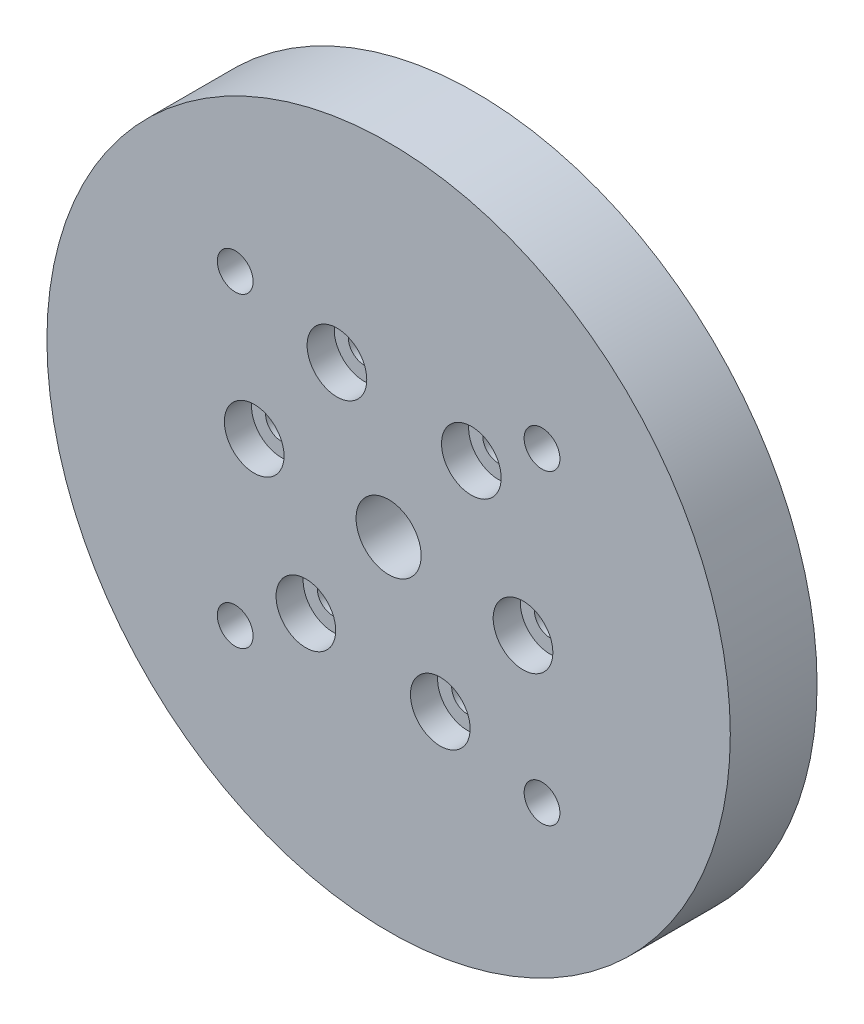
SolidWorks part; units mm, degrees
material "Aleación 6061"
ref_plane "Alzado" through (0, 0, 0) normal (0, 0, 1) x (1, 0, 0)
ref_plane "Planta" through (0, 0, 0) normal (0, 1, 0) x (1, 0, 0)
ref_plane "Vista lateral" through (0, 0, 0) normal (1, 0, 0) x (0, 0, -1)
sketch "Sk_Brida" plane through (0, 0, 0) normal (0, 0, 1) x (1, 0, 0)
  circle A0 centre (0, 0) radius 31.5
  dimension "D1" = 63
extrude "Brida" add sketch "Sk_Brida" along normal blind 8 from offset 567
sketch "Sk_Centro" plane through (0, 0, 0) normal (0, 0, 1) x (1, 0, 0)
  circle A0 centre (0, 0) radius 3
  dimension "D1" = 6
extrude "Centro" cut sketch "Sk_Centro" along normal blind 8 from offset 567
sketch "Sk_Roscas_M4_herramienta" plane through (0, 0, 0) normal (0, 0, 1) x (1, 0, 0)
  circle A0 centre (14.1421, 14.1421) radius 1.65
  circle A1 centre (-14.1421, 14.1421) radius 1.65
  circle A2 centre (-14.1421, -14.1421) radius 1.65
  circle A3 centre (14.1421, -14.1421) radius 1.65
  dimension "D1" = 3.3
  dimension "D4" = 3.3
  dimension "D7" = 3.3
  dimension "D10" = 3.3
  dimension "D2" = 14.1421
  dimension "D3" = 14.1421
  dimension "D5" = 14.1421
  dimension "D6" = 14.1421
  dimension "D8" = 14.1421
  dimension "D9" = 14.1421
  dimension "D11" = 14.1421
  dimension "D12" = 14.1421
extrude "Roscas_M4_herramienta" cut sketch "Sk_Roscas_M4_herramienta" along normal blind 8 from offset 567
sketch "Sk_Pasantes_M2-5_rotor_J6" plane through (0, 0, 0) normal (0, 0, 1) x (1, 0, 0)
  circle A0 centre (12.3902, -1.6532) radius 1.45
  circle A1 centre (7.6268, 9.9036) radius 1.45
  circle A2 centre (-4.7634, 11.5568) radius 1.45
  circle A3 centre (-12.3902, 1.6532) radius 1.45
  circle A4 centre (-7.6268, -9.9036) radius 1.45
  circle A5 centre (4.7634, -11.5568) radius 1.45
  dimension "D1" = 2.9
  dimension "D4" = 2.9
  dimension "D7" = 2.9
  dimension "D10" = 2.9
  dimension "D13" = 2.9
  dimension "D16" = 2.9
  dimension "D2" = 12.3902
  dimension "D3" = 1.6532
  dimension "D5" = 7.6268
  dimension "D6" = 9.9036
  dimension "D8" = 4.7634
  dimension "D9" = 11.5568
  dimension "D11" = 12.3902
  dimension "D12" = 1.6532
  dimension "D14" = 7.6268
  dimension "D15" = 9.9036
  dimension "D17" = 4.7634
  dimension "D18" = 11.5568
extrude "Pasantes_M2-5_rotor_J6" cut sketch "Sk_Pasantes_M2-5_rotor_J6" along normal blind 8 from offset 567
sketch "Sk_Cajas_M2-5" plane through (0, 0, 0) normal (0, 0, 1) x (1, 0, 0)
  circle A0 centre (12.3902, -1.6532) radius 2.75
  circle A1 centre (7.6268, 9.9036) radius 2.75
  circle A2 centre (-4.7634, 11.5568) radius 2.75
  circle A3 centre (-12.3902, 1.6532) radius 2.75
  circle A4 centre (-7.6268, -9.9036) radius 2.75
  circle A5 centre (4.7634, -11.5568) radius 2.75
  dimension "D1" = 5.5
  dimension "D4" = 5.5
  dimension "D7" = 5.5
  dimension "D10" = 5.5
  dimension "D13" = 5.5
  dimension "D16" = 5.5
  dimension "D2" = 12.3902
  dimension "D3" = 1.6532
  dimension "D5" = 7.6268
  dimension "D6" = 9.9036
  dimension "D8" = 4.7634
  dimension "D9" = 11.5568
  dimension "D11" = 12.3902
  dimension "D12" = 1.6532
  dimension "D14" = 7.6268
  dimension "D15" = 9.9036
  dimension "D17" = 4.7634
  dimension "D18" = 11.5568
extrude "Cajas_M2-5" cut sketch "Sk_Cajas_M2-5" along normal blind 2.5 from offset 572.5
